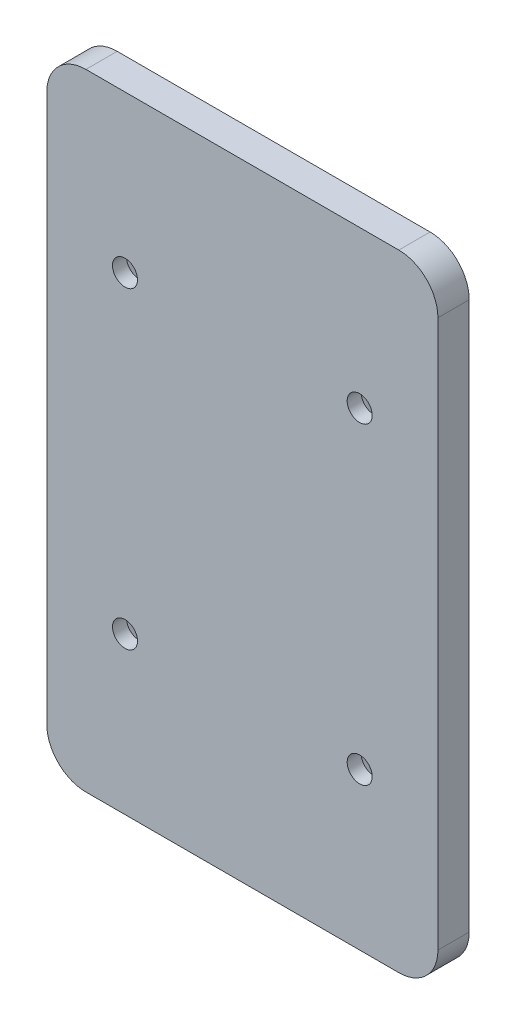
SolidWorks part; units mm, degrees
ref_plane "Płaszczyzna przednia" through (0, 0, 0) normal (0, 0, 1) x (1, 0, 0)
ref_plane "Płaszczyzna górna" through (0, 0, 0) normal (0, 1, 0) x (1, 0, 0)
ref_plane "Płaszczyzna prawa" through (0, 0, 0) normal (1, 0, 0) x (0, 0, -1)
sketch "Szkic1" plane through (0, 0, 0) normal (0, 0, 1) x (1, 0, 0)
  line L1 (-20, -40) -> (20, -40)
  line L2 (-25, -35) -> (-25, 35)
  line L3 (-20, 40) -> (20, 40)
  line L4 (25, -35) -> (25, 35)
  line L5 (-25, -40) -> (25, 40) construction
  line L6 (-25, 40) -> (25, -40) construction
  arc A0 (-25, -35) -> (-20, -40) centre (-20, -35) ccw
  arc A1 (20, -40) -> (25, -35) centre (20, -35) ccw
  arc A2 (25, 35) -> (20, 40) centre (20, 35) ccw
  arc A3 (-20, 40) -> (-25, 35) centre (-20, 35) ccw
  point P0 (0, 0)
  dimension "D1" = 5
  dimension "D2" = 80
  dimension "D3" = 50
extrude "Dodanie-wyciągnięcie1" add sketch "Szkic1" along normal blind 4
sketch "Szkic2" plane through (0, 0, 0) normal (0, 0, -1) x (-1, 0, 0)
  line L0 (0, -40) -> (0, 40) construction
  line L1 (20, -40) -> (-20, -40) construction
  line L2 (-20, 40) -> (20, 40) construction
  line L3 (25, 0) -> (-25, 0) construction
  line L4 (25, 35) -> (25, -35) construction
  line L5 (-25, -35) -> (-25, 35) construction
  circle A0 centre (-15, 20) radius 1.6
  circle A1 centre (15, 20) radius 1.6
  circle A2 centre (15, -20) radius 1.6
  circle A3 centre (-15, -20) radius 1.6
  dimension "D1" = 3.2
  dimension "D2" = 15
  dimension "D3" = 40
extrude "Wytnij-wyciągnięcie1" cut sketch "Szkic2" against normal up to next
sketch "Szkic3" plane through (0, 0, 0) normal (0, 0, -1) x (-1, 0, 0)
  line L0 (0, 40) -> (0, -40) construction
  line L1 (-11.7091, 20) -> (-13.3546, 22.85)
  line L2 (-13.3546, 22.85) -> (-16.6454, 22.85)
  line L3 (-16.6454, 22.85) -> (-18.2909, 20)
  line L4 (-18.2909, 20) -> (-16.6454, 17.15)
  line L5 (-16.6454, 17.15) -> (-13.3546, 17.15)
  line L6 (-13.3546, 17.15) -> (-11.7091, 20)
  line L7 (-20, 40) -> (20, 40) construction
  line L8 (20, -40) -> (-20, -40) construction
  line L9 (25, 0) -> (-25, 0) construction
  line L10 (25, 35) -> (25, -35) construction
  line L11 (-25, -35) -> (-25, 35) construction
  line L12 (13.3546, 17.15) -> (11.7091, 20)
  line L13 (16.6454, 17.15) -> (13.3546, 17.15)
  line L14 (18.2909, 20) -> (16.6454, 17.15)
  line L15 (16.6454, 22.85) -> (18.2909, 20)
  line L16 (13.3546, 22.85) -> (16.6454, 22.85)
  line L17 (11.7091, 20) -> (13.3546, 22.85)
  line L18 (11.7091, -20) -> (13.3546, -22.85)
  line L19 (13.3546, -22.85) -> (16.6454, -22.85)
  line L20 (16.6454, -22.85) -> (18.2909, -20)
  line L21 (18.2909, -20) -> (16.6454, -17.15)
  line L22 (16.6454, -17.15) -> (13.3546, -17.15)
  line L23 (13.3546, -17.15) -> (11.7091, -20)
  line L24 (-13.3546, -17.15) -> (-11.7091, -20)
  line L25 (-16.6454, -17.15) -> (-13.3546, -17.15)
  line L26 (-18.2909, -20) -> (-16.6454, -17.15)
  line L27 (-16.6454, -22.85) -> (-18.2909, -20)
  line L28 (-13.3546, -22.85) -> (-16.6454, -22.85)
  line L29 (-11.7091, -20) -> (-13.3546, -22.85)
  circle A0 centre (-15, 20) radius 2.85 construction
  circle A1 centre (-15, 20) radius 1.6
  circle A2 centre (15, 20) radius 1.6
  circle A3 centre (-15, -20) radius 2.85 construction
  circle A4 centre (15, -20) radius 1.6
  circle A5 centre (-15, -20) radius 1.6
  dimension "D2" = 3.2
  dimension "D1" = 5.7
extrude "Wytnij-wyciągnięcie2" cut sketch "Szkic3" against normal blind 2.2
